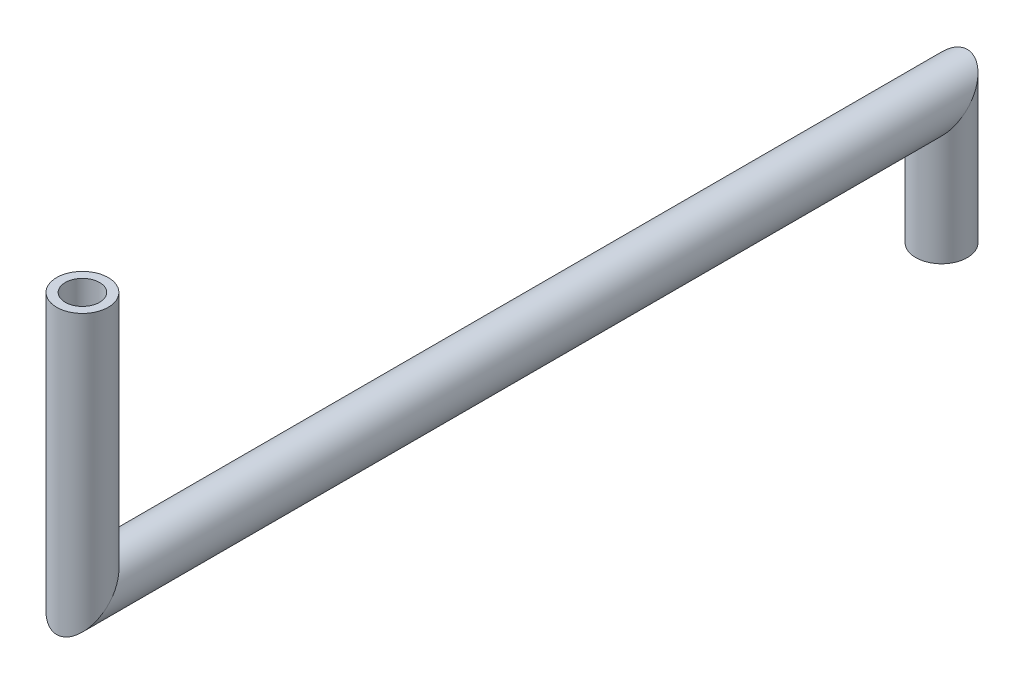
SolidWorks part; units mm, degrees
ref_plane "Front Plane" through (0, 0, 0) normal (0, 0, 1) x (1, 0, 0)
ref_plane "Top Plane" through (0, 0, 0) normal (0, 1, 0) x (1, 0, 0)
ref_plane "Right Plane" through (0, 0, 0) normal (1, 0, 0) x (0, 0, -1)
sketch "Sketch1" plane through (0, 0, 0) normal (1, 0, 0) x (0, 0, -1)
  line L0 (0, 0) -> (0, 300)
  line L1 (0, 300) -> (-2000, 300)
  line L2 (-2000, 300) -> (-2000, 900)
  point P3 (-2000, 600)
  dimension "D1" = 300
  dimension "D2" = 300
  dimension "D3" = 2000
sketch "Sketch4" plane through (0, 0, 0) normal (0, 1, 0) x (1, 0, 0)
  circle A0 centre (0, 0) radius 40
  circle A1 centre (0, 0) radius 60
  point P4 (0, 0)
  dimension "D1" = 80
  dimension "D2" = 120
sweep "Sweep1" add profiles "Sketch4" path "Sketch1"
